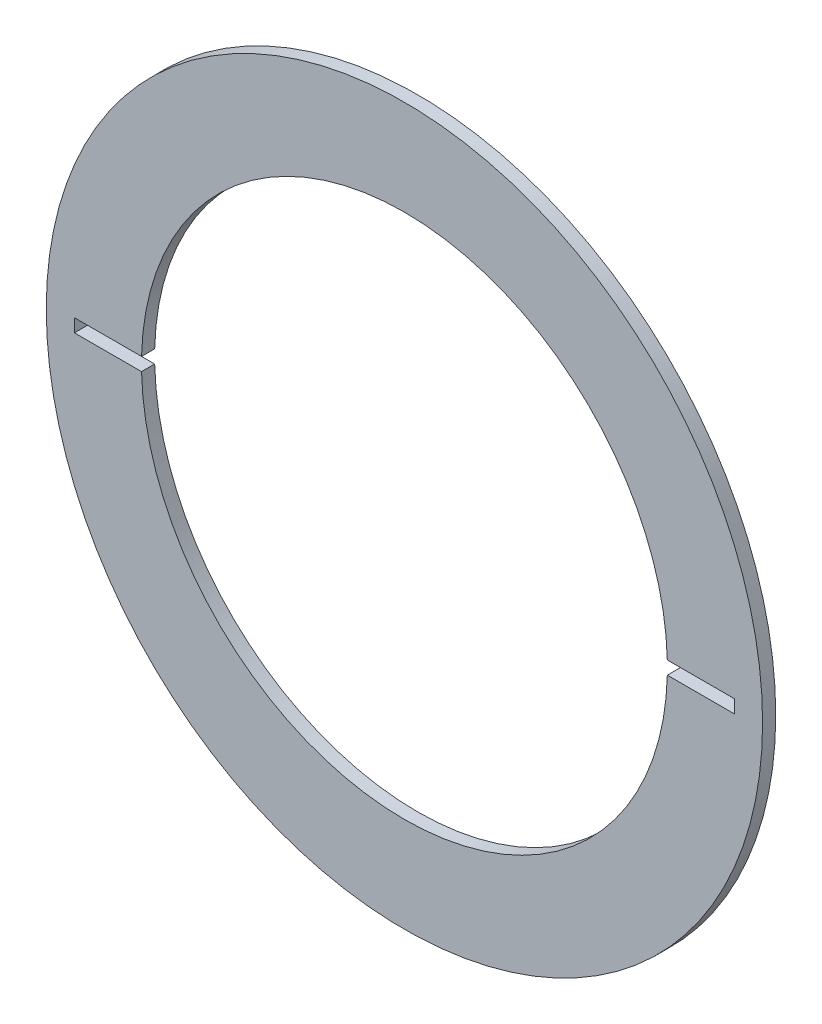
SolidWorks part; units mm, degrees
material "E-Glass Fiber"
ref_plane "Front Plane" through (0, 0, 0) normal (0, 0, 1) x (1, 0, 0)
ref_plane "Top Plane" through (0, 0, 0) normal (0, 1, 0) x (1, 0, 0)
ref_plane "Right Plane" through (0, 0, 0) normal (1, 0, 0) x (0, 0, -1)
sketch "Sketch1" plane through (0, 0, 0) normal (0, 0, 1) x (1, 0, 0)
  line L1 (39.845, -0.7937) -> (-39.845, -0.7938)
  line L2 (39.845, -0.7937) -> (39.845, 0.7938)
  line L3 (39.845, 0.7938) -> (-39.845, 0.7937)
  line L4 (-39.845, -0.7938) -> (-39.845, 0.7937)
  line L5 (39.845, -0.7937) -> (-39.845, 0.7937) construction
  line L6 (39.845, 0.7938) -> (-39.845, -0.7938) construction
  circle A0 centre (0, 0) radius 43.2435
  circle A1 centre (0, 0) radius 31.75
  dimension "D1" = 86.487
  dimension "D2" = 63.5
  dimension "D3" = 79.69
  dimension "D4" = 1.5875
extrude "Boss-Extrude1" add sketch "Sketch1" along normal blind 1.5875 contours A0 A1 L3 L2 L1 L4
